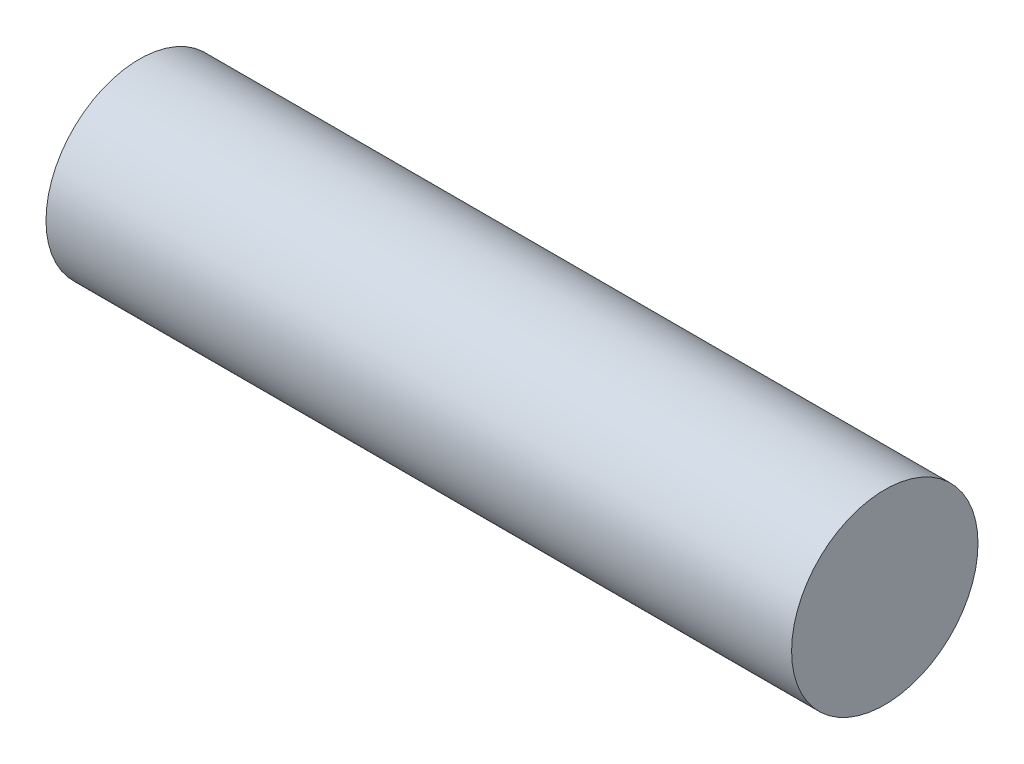
SolidWorks part; units mm, degrees
ref_plane "Front Plane" through (0, 0, 0) normal (0, 0, 1) x (1, 0, 0)
ref_plane "Top Plane" through (0, 0, 0) normal (0, 1, 0) x (1, 0, 0)
ref_plane "Right Plane" through (0, 0, 0) normal (1, 0, 0) x (0, 0, -1)
sketch "Sketch1" plane through (0, 0, 0) normal (1, 0, 0) x (0, 0, -1)
  circle A0 centre (0, 0) radius 3.175
extrude "Boss-Extrude1" add sketch "Sketch1" along normal blind 25.4
